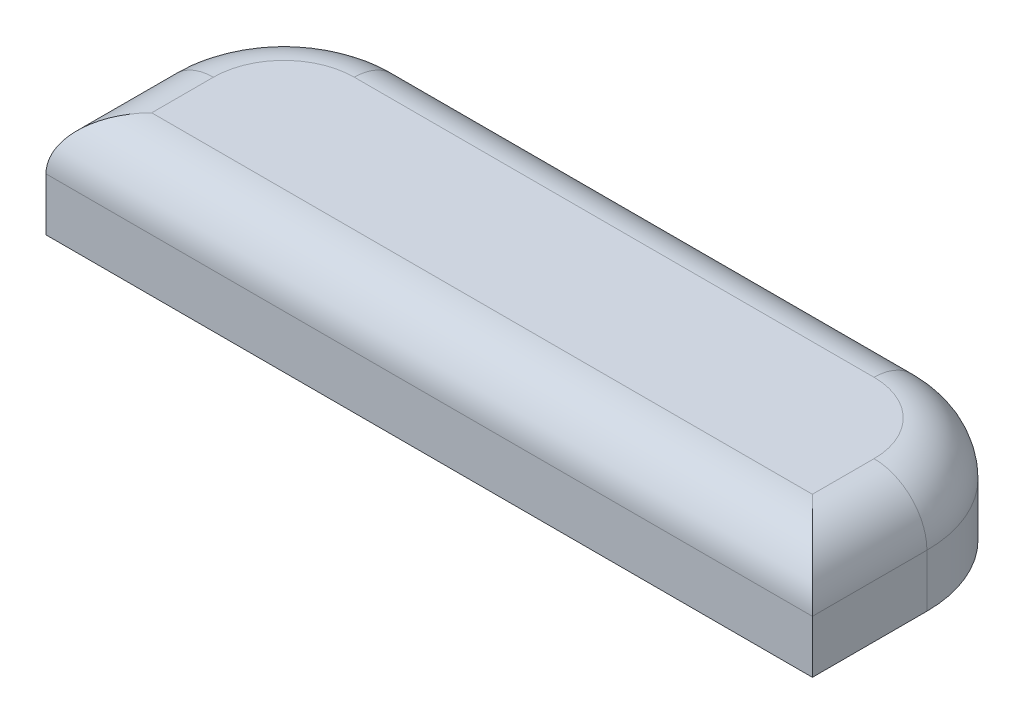
SolidWorks part; units mm, degrees
ref_plane "Front Plane" through (0, 0, 0) normal (0, 0, 1) x (1, 0, 0)
ref_plane "Top Plane" through (0, 0, 0) normal (0, 1, 0) x (1, 0, 0)
ref_plane "Right Plane" through (0, 0, 0) normal (1, 0, 0) x (0, 0, -1)
sketch "Sketch1" plane through (0, -295.7815, 0) normal (0, 1, 0) x (1, 0, 0)
  line L4 (469.578, -27) -> (469.578, -14)
  line L5 (455.578, 0) -> (396.578, 0)
  line L6 (382.578, -14) -> (382.578, -27)
  line L7 (382.578, -27) -> (469.578, -27)
  line L8 (469.578, -27) -> (469.578, -14)
  line L9 (455.578, 0) -> (396.578, 0)
  line L10 (382.578, -14) -> (382.578, -27)
  line L11 (382.578, -27) -> (469.578, -27)
  arc A2 (469.578, -14) -> (455.578, 0) centre (455.578, -14) ccw
  arc A3 (396.578, 0) -> (382.578, -14) centre (396.578, -14) ccw
  arc A4 (469.578, -14) -> (455.578, 0) centre (455.578, -14) ccw
  arc A5 (396.578, 0) -> (382.578, -14) centre (396.578, -14) ccw
  dimension "D1" = 0
extrude "Boss-Extrude1" add sketch "Sketch1" along normal blind 12
fillet "Fillet2" radius 6 6 edges at (382.578, -283.7815, 20.5) (386.6785, -283.7815, 4.1005) (426.078, -283.7815, 0) (465.4775, -283.7815, 4.1005) (469.578, -283.7815, 20.5) (426.078, -283.7815, 27)
